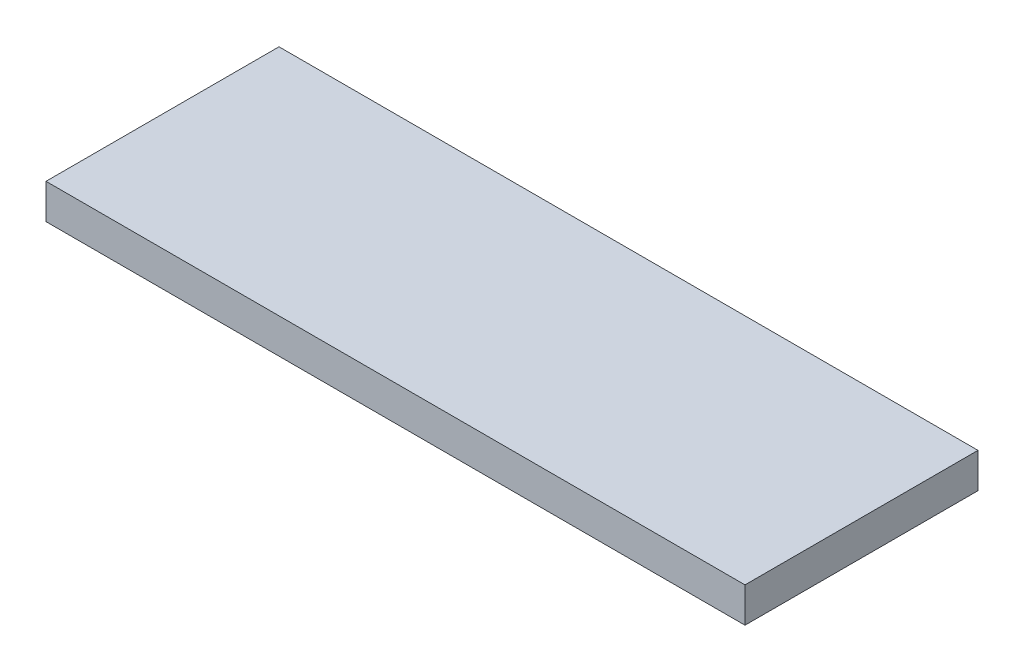
SolidWorks part; units mm, degrees
ref_plane "Front Plane" through (0, 0, 0) normal (0, 0, 1) x (1, 0, 0)
ref_plane "Top Plane" through (0, 0, 0) normal (0, 1, 0) x (1, 0, 0)
ref_plane "Right Plane" through (0, 0, 0) normal (1, 0, 0) x (0, 0, -1)
sketch "Sketch1" plane through (0, 0, 0) normal (0, 1, 0) x (1, 0, 0)
  line L1 (0, 0) -> (60, 0)
  line L2 (0, 0) -> (0, 20)
  line L3 (0, 20) -> (60, 20)
  line L4 (60, 0) -> (60, 20)
  dimension "D1" = 60
  dimension "D2" = 20
extrude "Boss-Extrude1" add sketch "Sketch1" along normal blind 3
